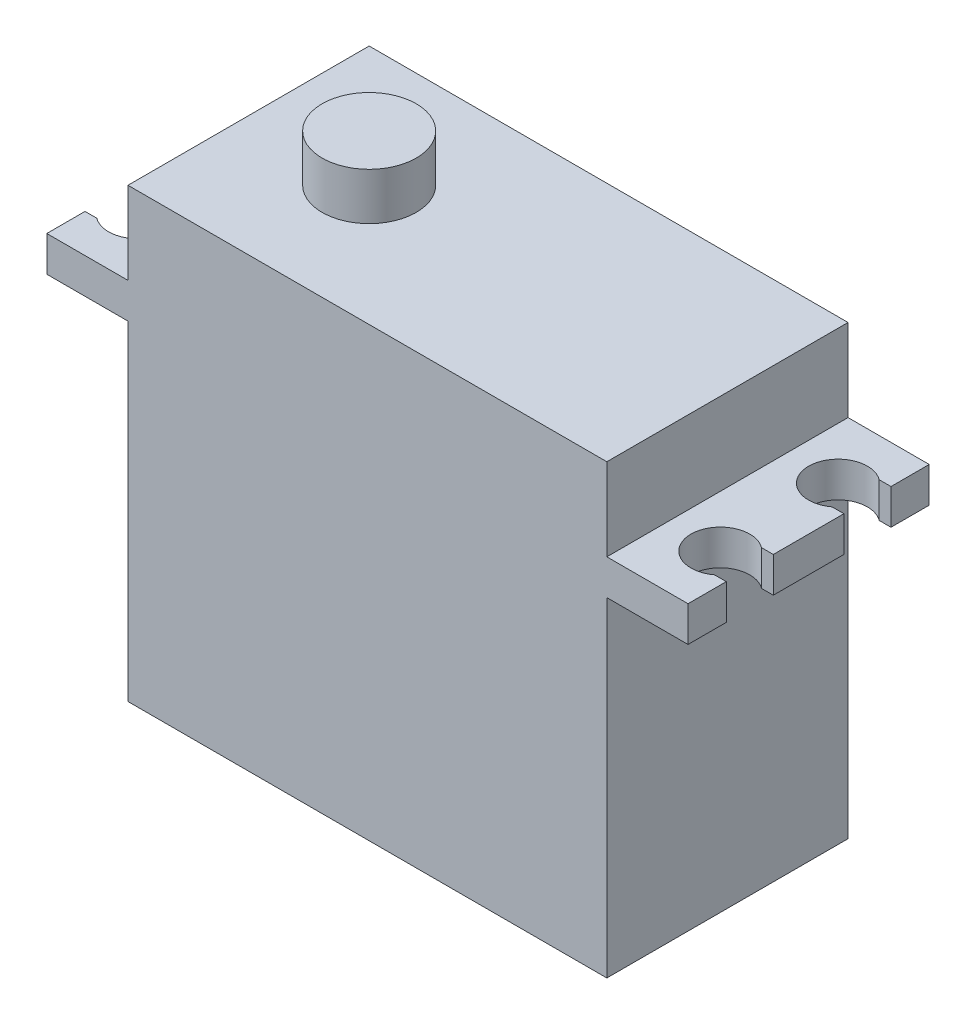
SolidWorks part; units mm, degrees
ref_plane "Front Plane" through (0, 0, 0) normal (0, 0, 1) x (1, 0, 0)
ref_plane "Top Plane" through (0, 0, 0) normal (0, 1, 0) x (1, 0, 0)
ref_plane "Right Plane" through (0, 0, 0) normal (1, 0, 0) x (0, 0, -1)
sketch "Sketch1" plane through (0, 0, 0) normal (0, 1, 0) x (1, 0, 0)
  line L1 (0, 0) -> (40.7, 0)
  line L2 (0, 0) -> (0, 20.5)
  line L3 (0, 20.5) -> (40.7, 20.5)
  line L4 (40.7, 0) -> (40.7, 20.5)
  dimension "D1" = 40.7
  dimension "D2" = 20.5
extrude "Boss-Extrude1" add sketch "Sketch1" along normal blind 38
sketch "Sketch2" plane through (0, 38, 0) normal (0, 1, 0) x (1, 0, 0)
  line L0 (0, 20.5) -> (0, 0) construction
  line L1 (40.7, 20.5) -> (0, 20.5) construction
  circle A0 centre (10.25, 10.25) radius 4
  dimension "D3" = 8
  dimension "D1" = 10.25
  dimension "D2" = 10.25
extrude "Boss-Extrude2" add sketch "Sketch2" along normal offset from surface (4 mm away) 42 up to face at (20.35, 0, -10.25)
ref_plane "Plane1" through (0, 28, 0) normal (0, 1, 0) x (1, 0, 0)
sketch "Sketch3" plane through (0, 28, 0) normal (0, 1, 0) x (1, 0, 0)
  line L0 (40.7, 20.5) -> (0, 20.5) construction
  line L1 (-6.9, 20.5) -> (47.6, 20.5)
  line L2 (-6.9, 20.5) -> (-6.9, 0)
  line L3 (-6.9, 0) -> (47.6, 0)
  line L4 (47.6, 20.5) -> (47.6, 0)
  line L5 (0, 0) -> (40.7, 0) construction
  point P8 (20.35, 0)
  point P9 (20.35, 0)
  dimension "D1" = 54.5
extrude "Boss-Extrude3" add sketch "Sketch3" along normal blind 3
sketch "Sketch4" plane through (0, 28, 0) normal (0, 1, 0) x (1, 0, 0)
  line L1 (40.7, 20.5) -> (0, 20.5) construction
  line L2 (-5.9, 17.25) -> (-6.9, 17.25)
  line L3 (-6.9, 20.5) -> (-6.9, 0) construction
  line L4 (-6.9, 17.25) -> (-6.9, 13.25)
  line L5 (-6.9, 13.25) -> (-5.9, 13.25)
  circle A0 centre (10.25, 10.25) radius 4 construction
  arc A2 (-5.9, 13.25) -> (-5.9, 17.25) centre (-4.4, 15.25) ccw
  point P15 (20.35, 20.5)
  dimension "D4" = 5
  dimension "D6" = 24.75
  dimension "D1" = 5
  dimension "D7" = 4
  dimension "D8" = 2
extrude "Cut-Extrude1" cut sketch "Sketch4" along normal through all
ref_plane "Plane2" through (0, 0, -10.25) normal (0, 0, -1) x (-1, 0, 0)
ref_plane "Plane3" through (20.35, 0, 0) normal (1, 0, 0) x (0, 0, -1)
mirror "Mirror1" about plane through (0, 0, -10.25) normal (0, 0, -1) of "Cut-Extrude1"
mirror "Mirror2" about plane through (20.35, 0, 0) normal (1, 0, 0) of "Mirror1", "Cut-Extrude1"
